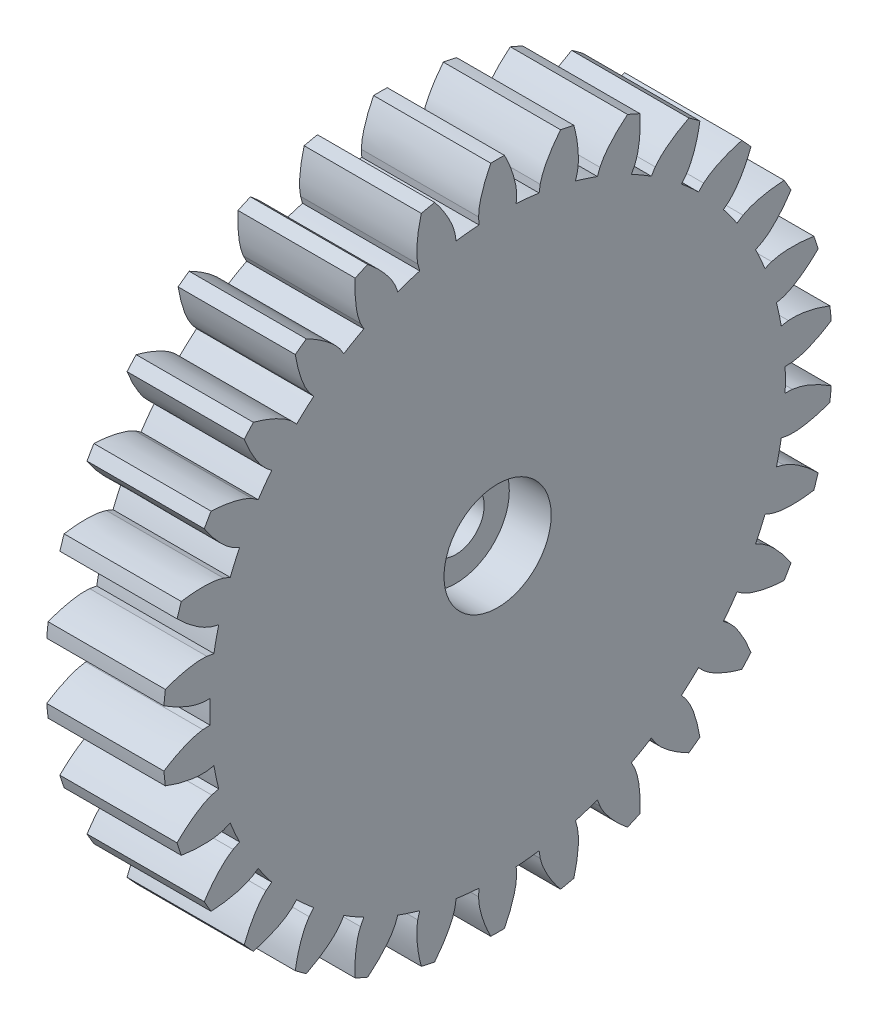
SolidWorks part; units mm, degrees
ref_plane "Front Plane" through (0, 0, 0) normal (0, 0, 1) x (1, 0, 0)
ref_plane "Top Plane" through (0, 0, 0) normal (0, 1, 0) x (1, 0, 0)
ref_plane "Right Plane" through (0, 0, 0) normal (1, 0, 0) x (0, 0, -1)
sketch "Sketch1" plane through (0, 0, 0) normal (1, 0, 0) x (0, 0, -1)
  line L0 (21.6583, 105.3963) -> (21.2327, 105.469)
  line L1 (20.9949, 103.2067) -> (21.4263, 103.1894)
  line L2 (21.4263, 101.8106) -> (20.9949, 101.7933)
  line L3 (21.2327, 99.531) -> (21.6583, 99.6037)
  line L4 (21.945, 98.255) -> (21.5266, 98.1484)
  line L5 (22.2295, 95.985) -> (22.6307, 96.1447)
  line L6 (23.1915, 94.885) -> (22.8044, 94.6937)
  line L7 (23.9418, 92.7238) -> (24.301, 92.9633)
  line L8 (25.1114, 91.8478) -> (24.7726, 91.5802)
  line L9 (26.2947, 89.8898) -> (26.5962, 90.1988)
  line L10 (27.6209, 89.2762) -> (27.3451, 88.944)
  line L11 (29.1854, 87.6069) -> (29.4161, 87.9719)
  line L12 (30.6102, 87.2825) -> (30.4095, 86.9002)
  line L13 (32.4876, 85.975) -> (32.6374, 86.3799)
  line L14 (33.9487, 85.9538) -> (33.8319, 85.5382)
  line L15 (36.0569, 85.0653) -> (36.1192, 85.4925)
  line L16 (37.4905, 85.3483) -> (37.4626, 84.9175)
  line L17 (39.7374, 84.9175) -> (39.7095, 85.3483)
  line L18 (41.0808, 85.4925) -> (41.1431, 85.0653)
  line L19 (43.3681, 85.5382) -> (43.2513, 85.9538)
  line L20 (44.5626, 86.3799) -> (44.7124, 85.975)
  line L21 (46.7905, 86.9002) -> (46.5898, 87.2825)
  line L22 (47.7839, 87.9719) -> (48.0146, 87.6069)
  line L23 (49.8549, 88.944) -> (49.5791, 89.2762)
  line L24 (50.6038, 90.1988) -> (50.9053, 89.8898)
  line L25 (52.4274, 91.5802) -> (52.0886, 91.8478)
  line L26 (52.899, 92.9633) -> (53.2582, 92.7238)
  line L27 (54.3956, 94.6937) -> (54.0085, 94.885)
  line L28 (54.5693, 96.1447) -> (54.9705, 95.985)
  line L29 (55.6734, 98.1484) -> (55.255, 98.255)
  line L30 (55.5417, 99.6037) -> (55.9673, 99.531)
  line L31 (56.2051, 101.7933) -> (55.7737, 101.8106)
  line L32 (55.7737, 103.1894) -> (56.2051, 103.2067)
  line L33 (55.9673, 105.469) -> (55.5417, 105.3963)
  line L34 (55.255, 106.745) -> (55.6734, 106.8516)
  line L35 (54.9705, 109.015) -> (54.5693, 108.8553)
  line L36 (54.0085, 110.115) -> (54.3956, 110.3063)
  line L37 (53.2582, 112.2762) -> (52.899, 112.0367)
  line L38 (52.0886, 113.1522) -> (52.4274, 113.4198)
  line L39 (50.9053, 115.1102) -> (50.6038, 114.8012)
  line L40 (49.5791, 115.7238) -> (49.8549, 116.056)
  line L41 (48.0146, 117.3931) -> (47.7839, 117.0281)
  line L42 (46.5898, 117.7175) -> (46.7905, 118.0998)
  line L43 (44.7124, 119.025) -> (44.5626, 118.6201)
  line L44 (43.2513, 119.0462) -> (43.3681, 119.4618)
  line L45 (41.1431, 119.9347) -> (41.0808, 119.5075)
  line L46 (39.7095, 119.6517) -> (39.7374, 120.0825)
  line L47 (37.4626, 120.0825) -> (37.4905, 119.6517)
  line L48 (36.1192, 119.5075) -> (36.0569, 119.9347)
  line L49 (33.8319, 119.4618) -> (33.9487, 119.0462)
  line L50 (32.6374, 118.6201) -> (32.4876, 119.025)
  line L51 (30.4095, 118.0998) -> (30.6102, 117.7175)
  line L52 (29.4161, 117.0281) -> (29.1854, 117.3931)
  line L53 (27.3451, 116.056) -> (27.6209, 115.7238)
  line L54 (26.5962, 114.8012) -> (26.2947, 115.1102)
  line L55 (24.7726, 113.4198) -> (25.1114, 113.1522)
  line L56 (24.301, 112.0367) -> (23.9418, 112.2762)
  line L57 (22.8044, 110.3063) -> (23.1915, 110.115)
  line L58 (22.6307, 108.8553) -> (22.2295, 109.015)
  line L59 (21.5266, 106.8516) -> (21.945, 106.745)
  arc A0 (18.7563, 104.9954) -> (18.6711, 104.1849) centre (38.6, 102.5) ccw
  arc A1 (21.4263, 103.1894) -> (21.4263, 101.8106) centre (38.6, 102.5) ccw
  arc A2 (18.6711, 100.8151) -> (18.7563, 100.0046) centre (38.6, 102.5) ccw
  arc A3 (21.6583, 99.6037) -> (21.945, 98.255) centre (38.6, 102.5) ccw
  arc A4 (19.4569, 96.7085) -> (19.7087, 95.9334) centre (38.6, 102.5) ccw
  arc A5 (22.6307, 96.1447) -> (23.1915, 94.885) centre (38.6, 102.5) ccw
  arc A6 (21.0793, 92.855) -> (21.4868, 92.1492) centre (38.6, 102.5) ccw
  arc A7 (24.301, 92.9633) -> (25.1114, 91.8478) centre (38.6, 102.5) ccw
  arc A8 (23.4675, 89.423) -> (24.0129, 88.8173) centre (38.6, 102.5) ccw
  arc A9 (26.5962, 90.1988) -> (27.6209, 89.2762) centre (38.6, 102.5) ccw
  arc A10 (26.5171, 86.5625) -> (27.1764, 86.0835) centre (38.6, 102.5) ccw
  arc A11 (29.4161, 87.9719) -> (30.6102, 87.2825) centre (38.6, 102.5) ccw
  arc A12 (30.0947, 84.3986) -> (30.8392, 84.0671) centre (38.6, 102.5) ccw
  arc A13 (32.6374, 86.3799) -> (33.9487, 85.9538) centre (38.6, 102.5) ccw
  arc A14 (34.044, 83.0258) -> (34.8412, 82.8564) centre (38.6, 102.5) ccw
  arc A15 (36.1192, 85.4925) -> (37.4905, 85.3483) centre (38.6, 102.5) ccw
  arc A16 (38.1925, 82.5042) -> (39.0075, 82.5042) centre (38.6, 102.5) ccw
  arc A17 (39.7095, 85.3483) -> (41.0808, 85.4925) centre (38.6, 102.5) ccw
  arc A18 (42.3588, 82.8564) -> (43.156, 83.0258) centre (38.6, 102.5) ccw
  arc A19 (43.2513, 85.9538) -> (44.5626, 86.3799) centre (38.6, 102.5) ccw
  arc A20 (46.3608, 84.0671) -> (47.1053, 84.3986) centre (38.6, 102.5) ccw
  arc A21 (46.5898, 87.2825) -> (47.7839, 87.9719) centre (38.6, 102.5) ccw
  arc A22 (50.0236, 86.0835) -> (50.6829, 86.5625) centre (38.6, 102.5) ccw
  arc A23 (49.5791, 89.2762) -> (50.6038, 90.1988) centre (38.6, 102.5) ccw
  arc A24 (53.1871, 88.8173) -> (53.7325, 89.423) centre (38.6, 102.5) ccw
  arc A25 (52.0886, 91.8478) -> (52.899, 92.9633) centre (38.6, 102.5) ccw
  arc A26 (55.7132, 92.1492) -> (56.1207, 92.855) centre (38.6, 102.5) ccw
  arc A27 (54.0085, 94.885) -> (54.5693, 96.1447) centre (38.6, 102.5) ccw
  arc A28 (57.4913, 95.9334) -> (57.7431, 96.7085) centre (38.6, 102.5) ccw
  arc A29 (55.255, 98.255) -> (55.5417, 99.6037) centre (38.6, 102.5) ccw
  arc A30 (58.4437, 100.0046) -> (58.5289, 100.8151) centre (38.6, 102.5) ccw
  arc A31 (55.7737, 101.8106) -> (55.7737, 103.1894) centre (38.6, 102.5) ccw
  arc A32 (58.5289, 104.1849) -> (58.4437, 104.9954) centre (38.6, 102.5) ccw
  arc A33 (55.5417, 105.3963) -> (55.255, 106.745) centre (38.6, 102.5) ccw
  arc A34 (57.7431, 108.2915) -> (57.4913, 109.0666) centre (38.6, 102.5) ccw
  arc A35 (54.5693, 108.8553) -> (54.0085, 110.115) centre (38.6, 102.5) ccw
  arc A36 (56.1207, 112.145) -> (55.7132, 112.8508) centre (38.6, 102.5) ccw
  arc A37 (52.899, 112.0367) -> (52.0886, 113.1522) centre (38.6, 102.5) ccw
  arc A38 (53.7325, 115.577) -> (53.1871, 116.1827) centre (38.6, 102.5) ccw
  arc A39 (50.6038, 114.8012) -> (49.5791, 115.7238) centre (38.6, 102.5) ccw
  arc A40 (50.6829, 118.4375) -> (50.0236, 118.9165) centre (38.6, 102.5) ccw
  arc A41 (47.7839, 117.0281) -> (46.5898, 117.7175) centre (38.6, 102.5) ccw
  arc A42 (47.1053, 120.6014) -> (46.3608, 120.9329) centre (38.6, 102.5) ccw
  arc A43 (44.5626, 118.6201) -> (43.2513, 119.0462) centre (38.6, 102.5) ccw
  arc A44 (43.156, 121.9742) -> (42.3588, 122.1436) centre (38.6, 102.5) ccw
  arc A45 (41.0808, 119.5075) -> (39.7095, 119.6517) centre (38.6, 102.5) ccw
  arc A46 (39.0075, 122.4958) -> (38.1925, 122.4958) centre (38.6, 102.5) ccw
  arc A47 (37.4905, 119.6517) -> (36.1192, 119.5075) centre (38.6, 102.5) ccw
  arc A48 (34.8412, 122.1436) -> (34.044, 121.9742) centre (38.6, 102.5) ccw
  arc A49 (33.9487, 119.0462) -> (32.6374, 118.6201) centre (38.6, 102.5) ccw
  arc A50 (30.8392, 120.9329) -> (30.0947, 120.6014) centre (38.6, 102.5) ccw
  arc A51 (30.6102, 117.7175) -> (29.4161, 117.0281) centre (38.6, 102.5) ccw
  arc A52 (27.1764, 118.9165) -> (26.5171, 118.4375) centre (38.6, 102.5) ccw
  arc A53 (27.6209, 115.7238) -> (26.5962, 114.8012) centre (38.6, 102.5) ccw
  arc A54 (24.0129, 116.1827) -> (23.4675, 115.577) centre (38.6, 102.5) ccw
  arc A55 (25.1114, 113.1522) -> (24.301, 112.0367) centre (38.6, 102.5) ccw
  arc A56 (21.4868, 112.8508) -> (21.0793, 112.145) centre (38.6, 102.5) ccw
  arc A57 (23.1915, 110.115) -> (22.6307, 108.8553) centre (38.6, 102.5) ccw
  arc A58 (19.7087, 109.0666) -> (19.4569, 108.2915) centre (38.6, 102.5) ccw
  arc A59 (21.945, 106.745) -> (21.6583, 105.3963) centre (38.6, 102.5) ccw
  spline S0 degree 3 poles (21.2327, 105.469) (21.0719, 105.4759) (20.7459, 105.4898) (20.2535, 105.4223) (19.7559, 105.3195) (19.2537, 105.1778) (18.9234, 105.0567) (18.7563, 104.9954) knots 0 0 0 0 0.189678 0.384631 0.584678 0.789803 1 1 1 1
  spline S1 degree 3 poles (18.6711, 104.1849) (18.8219, 104.0902) (19.1197, 103.9031) (19.5815, 103.66) (20.0468, 103.456) (20.5145, 103.2876) (20.8363, 103.2335) (20.9949, 103.2067) knots 0 0 0 0 0.210197 0.415322 0.615369 0.810322 1 1 1 1
  spline S2 degree 3 poles (20.9949, 101.7933) (20.8363, 101.7665) (20.5145, 101.7124) (20.0468, 101.544) (19.5815, 101.34) (19.1197, 101.0969) (18.8219, 100.9098) (18.6711, 100.8151) knots 0 0 0 0 0.189678 0.384631 0.584678 0.789803 1 1 1 1
  spline S3 degree 3 poles (18.7563, 100.0046) (18.9234, 99.9433) (19.2537, 99.8222) (19.7559, 99.6805) (20.2535, 99.5777) (20.7459, 99.5102) (21.0719, 99.5241) (21.2327, 99.531) knots 0 0 0 0 0.210197 0.415322 0.615369 0.810322 1 1 1 1
  spline S4 degree 3 poles (21.5266, 98.1484) (21.3769, 98.0893) (21.0734, 97.9694) (20.651, 97.7074) (20.2383, 97.4111) (19.8371, 97.0774) (19.5847, 96.8325) (19.4569, 96.7085) knots 0 0 0 0 0.189678 0.384631 0.584678 0.789803 1 1 1 1
  spline S5 degree 3 poles (19.7087, 95.9334) (19.885, 95.9082) (20.2332, 95.8584) (20.7539, 95.8242) (21.262, 95.8271) (21.7577, 95.8635) (22.0737, 95.9449) (22.2295, 95.985) knots 0 0 0 0 0.210197 0.415322 0.615369 0.810322 1 1 1 1
  spline S6 degree 3 poles (22.8044, 94.6937) (22.6703, 94.6048) (22.3984, 94.4244) (22.0397, 94.0804) (21.6975, 93.7047) (21.3746, 93.2949) (21.1785, 93.0028) (21.0793, 92.855) knots 0 0 0 0 0.189678 0.384631 0.584678 0.789803 1 1 1 1
  spline S7 degree 3 poles (21.4868, 92.1492) (21.6645, 92.1612) (22.0154, 92.1849) (22.5318, 92.2597) (23.0282, 92.3682) (23.5055, 92.5068) (23.7977, 92.6521) (23.9418, 92.7238) knots 0 0 0 0 0.210197 0.415322 0.615369 0.810322 1 1 1 1
  spline S8 degree 3 poles (24.7726, 91.5802) (24.6599, 91.4654) (24.4315, 91.2324) (24.1521, 90.8213) (23.8955, 90.3827) (23.6648, 89.9147) (23.5338, 89.5882) (23.4675, 89.423) knots 0 0 0 0 0.189678 0.384631 0.584678 0.789803 1 1 1 1
  spline S9 degree 3 poles (24.0129, 88.8173) (24.1841, 88.866) (24.5225, 88.9622) (25.012, 89.1427) (25.475, 89.352) (25.9131, 89.5869) (26.1687, 89.7897) (26.2947, 89.8898) knots 0 0 0 0 0.210197 0.415322 0.615369 0.810322 1 1 1 1
  spline S10 degree 3 poles (27.3451, 88.944) (27.2588, 88.8082) (27.0837, 88.5328) (26.896, 88.0726) (26.7362, 87.5903) (26.6078, 87.0845) (26.5476, 86.7379) (26.5171, 86.5625) knots 0 0 0 0 0.189678 0.384631 0.584678 0.789803 1 1 1 1
  spline S11 degree 3 poles (27.1764, 86.0835) (27.3338, 86.1667) (27.6448, 86.3311) (28.0861, 86.6095) (28.4955, 86.9105) (28.8751, 87.2313) (29.0829, 87.4829) (29.1854, 87.6069) knots 0 0 0 0 0.210197 0.415322 0.615369 0.810322 1 1 1 1
  spline S12 degree 3 poles (30.4095, 86.9002) (30.3533, 86.7494) (30.2393, 86.4437) (30.1514, 85.9545) (30.0953, 85.4495) (30.0749, 84.9281) (30.088, 84.5765) (30.0947, 84.3986) knots 0 0 0 0 0.189678 0.384631 0.584678 0.789803 1 1 1 1
  spline S13 degree 3 poles (30.8392, 84.0671) (30.9759, 84.1813) (31.2459, 84.4067) (31.6197, 84.7708) (31.9575, 85.1503) (32.2622, 85.543) (32.4131, 85.8323) (32.4876, 85.975) knots 0 0 0 0 0.210197 0.415322 0.615369 0.810322 1 1 1 1
  spline S14 degree 3 poles (33.8319, 85.5382) (33.8083, 85.379) (33.7603, 85.0563) (33.776, 84.5595) (33.8262, 84.0538) (33.9146, 83.5396) (34.0005, 83.1985) (34.044, 83.0258) knots 0 0 0 0 0.189678 0.384631 0.584678 0.789803 1 1 1 1
  spline S15 degree 3 poles (34.8412, 82.8564) (34.9512, 82.9964) (35.1684, 83.2731) (35.4583, 83.7069) (35.7099, 84.1484) (35.9262, 84.5959) (36.0138, 84.9102) (36.0569, 85.0653) knots 0 0 0 0 0.210197 0.415322 0.615369 0.810322 1 1 1 1
  spline S16 degree 3 poles (37.4626, 84.9175) (37.4726, 84.7569) (37.4929, 84.4312) (37.6115, 83.9486) (37.7657, 83.4644) (37.9591, 82.9798) (38.1141, 82.664) (38.1925, 82.5042) knots 0 0 0 0 0.189678 0.384631 0.584678 0.789803 1 1 1 1
  spline S17 degree 3 poles (39.0075, 82.5042) (39.0859, 82.664) (39.2409, 82.9798) (39.4343, 83.4644) (39.5885, 83.9486) (39.7071, 84.4312) (39.7274, 84.7569) (39.7374, 84.9175) knots 0 0 0 0 0.210197 0.415322 0.615369 0.810322 1 1 1 1
  spline S18 degree 3 poles (41.1431, 85.0653) (41.1862, 84.9102) (41.2738, 84.5959) (41.4901, 84.1484) (41.7417, 83.7069) (42.0316, 83.2731) (42.2488, 82.9964) (42.3588, 82.8564) knots 0 0 0 0 0.189678 0.384631 0.584678 0.789803 1 1 1 1
  spline S19 degree 3 poles (43.156, 83.0258) (43.1995, 83.1985) (43.2854, 83.5396) (43.3738, 84.0538) (43.424, 84.5595) (43.4397, 85.0563) (43.3917, 85.379) (43.3681, 85.5382) knots 0 0 0 0 0.210197 0.415322 0.615369 0.810322 1 1 1 1
  spline S20 degree 3 poles (44.7124, 85.975) (44.7869, 85.8323) (44.9378, 85.543) (45.2425, 85.1503) (45.5803, 84.7708) (45.9541, 84.4067) (46.2241, 84.1813) (46.3608, 84.0671) knots 0 0 0 0 0.189678 0.384631 0.584678 0.789803 1 1 1 1
  spline S21 degree 3 poles (47.1053, 84.3986) (47.112, 84.5765) (47.1251, 84.9281) (47.1047, 85.4495) (47.0486, 85.9545) (46.9607, 86.4437) (46.8467, 86.7494) (46.7905, 86.9002) knots 0 0 0 0 0.210197 0.415322 0.615369 0.810322 1 1 1 1
  spline S22 degree 3 poles (48.0146, 87.6069) (48.1171, 87.4829) (48.3249, 87.2313) (48.7045, 86.9105) (49.1139, 86.6095) (49.5552, 86.3311) (49.8662, 86.1667) (50.0236, 86.0835) knots 0 0 0 0 0.189678 0.384631 0.584678 0.789803 1 1 1 1
  spline S23 degree 3 poles (50.6829, 86.5625) (50.6524, 86.7379) (50.5922, 87.0845) (50.4638, 87.5903) (50.304, 88.0726) (50.1163, 88.5328) (49.9412, 88.8082) (49.8549, 88.944) knots 0 0 0 0 0.210197 0.415322 0.615369 0.810322 1 1 1 1
  spline S24 degree 3 poles (50.9053, 89.8898) (51.0313, 89.7897) (51.2869, 89.5869) (51.725, 89.352) (52.188, 89.1427) (52.6775, 88.9622) (53.0159, 88.866) (53.1871, 88.8173) knots 0 0 0 0 0.189678 0.384631 0.584678 0.789803 1 1 1 1
  spline S25 degree 3 poles (53.7325, 89.423) (53.6662, 89.5882) (53.5352, 89.9147) (53.3045, 90.3827) (53.0479, 90.8213) (52.7685, 91.2324) (52.5401, 91.4654) (52.4274, 91.5802) knots 0 0 0 0 0.210197 0.415322 0.615369 0.810322 1 1 1 1
  spline S26 degree 3 poles (53.2582, 92.7238) (53.4023, 92.6521) (53.6945, 92.5068) (54.1718, 92.3682) (54.6682, 92.2597) (55.1846, 92.1849) (55.5355, 92.1612) (55.7132, 92.1492) knots 0 0 0 0 0.189678 0.384631 0.584678 0.789803 1 1 1 1
  spline S27 degree 3 poles (56.1207, 92.855) (56.0215, 93.0028) (55.8254, 93.2949) (55.5025, 93.7047) (55.1603, 94.0804) (54.8016, 94.4244) (54.5297, 94.6048) (54.3956, 94.6937) knots 0 0 0 0 0.210197 0.415322 0.615369 0.810322 1 1 1 1
  spline S28 degree 3 poles (54.9705, 95.985) (55.1263, 95.9449) (55.4423, 95.8635) (55.938, 95.8271) (56.4461, 95.8242) (56.9668, 95.8584) (57.315, 95.9082) (57.4913, 95.9334) knots 0 0 0 0 0.189678 0.384631 0.584678 0.789803 1 1 1 1
  spline S29 degree 3 poles (57.7431, 96.7085) (57.6153, 96.8325) (57.3629, 97.0774) (56.9617, 97.4111) (56.549, 97.7074) (56.1266, 97.9694) (55.8231, 98.0893) (55.6734, 98.1484) knots 0 0 0 0 0.210197 0.415322 0.615369 0.810322 1 1 1 1
  spline S30 degree 3 poles (55.9673, 99.531) (56.1281, 99.5241) (56.4541, 99.5102) (56.9465, 99.5777) (57.4441, 99.6805) (57.9463, 99.8222) (58.2766, 99.9433) (58.4437, 100.0046) knots 0 0 0 0 0.189678 0.384631 0.584678 0.789803 1 1 1 1
  spline S31 degree 3 poles (58.5289, 100.8151) (58.3781, 100.9098) (58.0803, 101.0969) (57.6185, 101.34) (57.1532, 101.544) (56.6855, 101.7124) (56.3637, 101.7665) (56.2051, 101.7933) knots 0 0 0 0 0.210197 0.415322 0.615369 0.810322 1 1 1 1
  spline S32 degree 3 poles (56.2051, 103.2067) (56.3637, 103.2335) (56.6855, 103.2876) (57.1532, 103.456) (57.6185, 103.66) (58.0803, 103.9031) (58.3781, 104.0902) (58.5289, 104.1849) knots 0 0 0 0 0.189678 0.384631 0.584678 0.789803 1 1 1 1
  spline S33 degree 3 poles (58.4437, 104.9954) (58.2766, 105.0567) (57.9463, 105.1778) (57.4441, 105.3195) (56.9465, 105.4223) (56.4541, 105.4898) (56.1281, 105.4759) (55.9673, 105.469) knots 0 0 0 0 0.210197 0.415322 0.615369 0.810322 1 1 1 1
  spline S34 degree 3 poles (55.6734, 106.8516) (55.8231, 106.9107) (56.1266, 107.0306) (56.549, 107.2926) (56.9617, 107.5889) (57.3629, 107.9226) (57.6153, 108.1675) (57.7431, 108.2915) knots 0 0 0 0 0.189678 0.384631 0.584678 0.789803 1 1 1 1
  spline S35 degree 3 poles (57.4913, 109.0666) (57.315, 109.0918) (56.9668, 109.1416) (56.4461, 109.1758) (55.938, 109.1729) (55.4423, 109.1365) (55.1263, 109.0551) (54.9705, 109.015) knots 0 0 0 0 0.210197 0.415322 0.615369 0.810322 1 1 1 1
  spline S36 degree 3 poles (54.3956, 110.3063) (54.5297, 110.3952) (54.8016, 110.5756) (55.1603, 110.9196) (55.5025, 111.2953) (55.8254, 111.7051) (56.0215, 111.9972) (56.1207, 112.145) knots 0 0 0 0 0.189678 0.384631 0.584678 0.789803 1 1 1 1
  spline S37 degree 3 poles (55.7132, 112.8508) (55.5355, 112.8388) (55.1846, 112.8151) (54.6682, 112.7403) (54.1718, 112.6318) (53.6945, 112.4932) (53.4023, 112.3479) (53.2582, 112.2762) knots 0 0 0 0 0.210197 0.415322 0.615369 0.810322 1 1 1 1
  spline S38 degree 3 poles (52.4274, 113.4198) (52.5401, 113.5346) (52.7685, 113.7676) (53.0479, 114.1787) (53.3045, 114.6173) (53.5352, 115.0853) (53.6662, 115.4118) (53.7325, 115.577) knots 0 0 0 0 0.189678 0.384631 0.584678 0.789803 1 1 1 1
  spline S39 degree 3 poles (53.1871, 116.1827) (53.0159, 116.134) (52.6775, 116.0378) (52.188, 115.8573) (51.725, 115.648) (51.2869, 115.4131) (51.0313, 115.2103) (50.9053, 115.1102) knots 0 0 0 0 0.210197 0.415322 0.615369 0.810322 1 1 1 1
  spline S40 degree 3 poles (49.8549, 116.056) (49.9412, 116.1918) (50.1163, 116.4672) (50.304, 116.9274) (50.4638, 117.4097) (50.5922, 117.9155) (50.6524, 118.2621) (50.6829, 118.4375) knots 0 0 0 0 0.189678 0.384631 0.584678 0.789803 1 1 1 1
  spline S41 degree 3 poles (50.0236, 118.9165) (49.8662, 118.8333) (49.5552, 118.6689) (49.1139, 118.3905) (48.7045, 118.0895) (48.3249, 117.7687) (48.1171, 117.5171) (48.0146, 117.3931) knots 0 0 0 0 0.210197 0.415322 0.615369 0.810322 1 1 1 1
  spline S42 degree 3 poles (46.7905, 118.0998) (46.8467, 118.2506) (46.9607, 118.5563) (47.0486, 119.0455) (47.1047, 119.5505) (47.1251, 120.0719) (47.112, 120.4235) (47.1053, 120.6014) knots 0 0 0 0 0.189678 0.384631 0.584678 0.789803 1 1 1 1
  spline S43 degree 3 poles (46.3608, 120.9329) (46.2241, 120.8187) (45.9541, 120.5933) (45.5803, 120.2292) (45.2425, 119.8497) (44.9378, 119.457) (44.7869, 119.1677) (44.7124, 119.025) knots 0 0 0 0 0.210197 0.415322 0.615369 0.810322 1 1 1 1
  spline S44 degree 3 poles (43.3681, 119.4618) (43.3917, 119.621) (43.4397, 119.9437) (43.424, 120.4405) (43.3738, 120.9462) (43.2854, 121.4604) (43.1995, 121.8015) (43.156, 121.9742) knots 0 0 0 0 0.189678 0.384631 0.584678 0.789803 1 1 1 1
  spline S45 degree 3 poles (42.3588, 122.1436) (42.2488, 122.0036) (42.0316, 121.7269) (41.7417, 121.2931) (41.4901, 120.8516) (41.2738, 120.4041) (41.1862, 120.0898) (41.1431, 119.9347) knots 0 0 0 0 0.210197 0.415322 0.615369 0.810322 1 1 1 1
  spline S46 degree 3 poles (39.7374, 120.0825) (39.7274, 120.2431) (39.7071, 120.5688) (39.5885, 121.0514) (39.4343, 121.5356) (39.2409, 122.0202) (39.0859, 122.336) (39.0075, 122.4958) knots 0 0 0 0 0.189678 0.384631 0.584678 0.789803 1 1 1 1
  spline S47 degree 3 poles (38.1925, 122.4958) (38.1141, 122.336) (37.9591, 122.0202) (37.7657, 121.5356) (37.6115, 121.0514) (37.4929, 120.5688) (37.4726, 120.2431) (37.4626, 120.0825) knots 0 0 0 0 0.210197 0.415322 0.615369 0.810322 1 1 1 1
  spline S48 degree 3 poles (36.0569, 119.9347) (36.0138, 120.0898) (35.9262, 120.4041) (35.7099, 120.8516) (35.4583, 121.2931) (35.1684, 121.7269) (34.9512, 122.0036) (34.8412, 122.1436) knots 0 0 0 0 0.189678 0.384631 0.584678 0.789803 1 1 1 1
  spline S49 degree 3 poles (34.044, 121.9742) (34.0005, 121.8015) (33.9146, 121.4604) (33.8262, 120.9462) (33.776, 120.4405) (33.7603, 119.9437) (33.8083, 119.621) (33.8319, 119.4618) knots 0 0 0 0 0.210197 0.415322 0.615369 0.810322 1 1 1 1
  spline S50 degree 3 poles (32.4876, 119.025) (32.4131, 119.1677) (32.2622, 119.457) (31.9575, 119.8497) (31.6197, 120.2292) (31.2459, 120.5933) (30.9759, 120.8187) (30.8392, 120.9329) knots 0 0 0 0 0.189678 0.384631 0.584678 0.789803 1 1 1 1
  spline S51 degree 3 poles (30.0947, 120.6014) (30.088, 120.4235) (30.0749, 120.0719) (30.0953, 119.5505) (30.1514, 119.0455) (30.2393, 118.5563) (30.3533, 118.2506) (30.4095, 118.0998) knots 0 0 0 0 0.210197 0.415322 0.615369 0.810322 1 1 1 1
  spline S52 degree 3 poles (29.1854, 117.3931) (29.0829, 117.5171) (28.8751, 117.7687) (28.4955, 118.0895) (28.0861, 118.3905) (27.6448, 118.6689) (27.3338, 118.8333) (27.1764, 118.9165) knots 0 0 0 0 0.189678 0.384631 0.584678 0.789803 1 1 1 1
  spline S53 degree 3 poles (26.5171, 118.4375) (26.5476, 118.2621) (26.6078, 117.9155) (26.7362, 117.4097) (26.896, 116.9274) (27.0837, 116.4672) (27.2588, 116.1918) (27.3451, 116.056) knots 0 0 0 0 0.210197 0.415322 0.615369 0.810322 1 1 1 1
  spline S54 degree 3 poles (26.2947, 115.1102) (26.1687, 115.2103) (25.9131, 115.4131) (25.475, 115.648) (25.012, 115.8573) (24.5225, 116.0378) (24.1841, 116.134) (24.0129, 116.1827) knots 0 0 0 0 0.189678 0.384631 0.584678 0.789803 1 1 1 1
  spline S55 degree 3 poles (23.4675, 115.577) (23.5338, 115.4118) (23.6648, 115.0853) (23.8955, 114.6173) (24.1521, 114.1787) (24.4315, 113.7676) (24.6599, 113.5346) (24.7726, 113.4198) knots 0 0 0 0 0.210197 0.415322 0.615369 0.810322 1 1 1 1
  spline S56 degree 3 poles (23.9418, 112.2762) (23.7977, 112.3479) (23.5055, 112.4932) (23.0282, 112.6318) (22.5318, 112.7403) (22.0154, 112.8151) (21.6645, 112.8388) (21.4868, 112.8508) knots 0 0 0 0 0.189678 0.384631 0.584678 0.789803 1 1 1 1
  spline S57 degree 3 poles (21.0793, 112.145) (21.1785, 111.9972) (21.3746, 111.7051) (21.6975, 111.2953) (22.0397, 110.9196) (22.3984, 110.5756) (22.6703, 110.3952) (22.8044, 110.3063) knots 0 0 0 0 0.210197 0.415322 0.615369 0.810322 1 1 1 1
  spline S58 degree 3 poles (22.2295, 109.015) (22.0737, 109.0551) (21.7577, 109.1365) (21.262, 109.1729) (20.7539, 109.1758) (20.2332, 109.1416) (19.885, 109.0918) (19.7087, 109.0666) knots 0 0 0 0 0.189678 0.384631 0.584678 0.789803 1 1 1 1
  spline S59 degree 3 poles (19.4569, 108.2915) (19.5847, 108.1675) (19.8371, 107.9226) (20.2383, 107.5889) (20.651, 107.2926) (21.0734, 107.0306) (21.3769, 106.9107) (21.5266, 106.8516) knots 0 0 0 0 0.210197 0.415322 0.615369 0.810322 1 1 1 1
extrude "Pinion 30T m1.25" add sketch "Sketch1" along normal blind 7 from offset 21.05
sketch "Sketch2" plane through (0, 0, 0) normal (1, 0, 0) x (0, 0, -1)
  line L0 (34.2, 91.4) -> (34.2, 113.6)
  line L1 (43, 113.6) -> (43, 91.4)
  arc A0 (34.2, 113.6) -> (43, 113.6) centre (38.6, 113.6) cw
  arc A1 (43, 91.4) -> (34.2, 91.4) centre (38.6, 91.4) cw
extrude "Trimmed-horn pocket" cut sketch "Sketch2" along normal blind 2.5 from offset 20.85
sketch "Sketch3" plane through (0, 0, 0) normal (1, 0, 0) x (0, 0, -1)
  circle A0 centre (38.6, 102.5) radius 1.7
extrude "M3 to shaft" cut sketch "Sketch3" along normal blind 7.4 from offset 20.85
sketch "Sketch4" plane through (0, 0, 0) normal (1, 0, 0) x (0, 0, -1)
  circle A0 centre (38.6, 102.5) radius 3.2
extrude "Head counterbore" cut sketch "Sketch4" along normal blind 2.7 from offset 25.55
